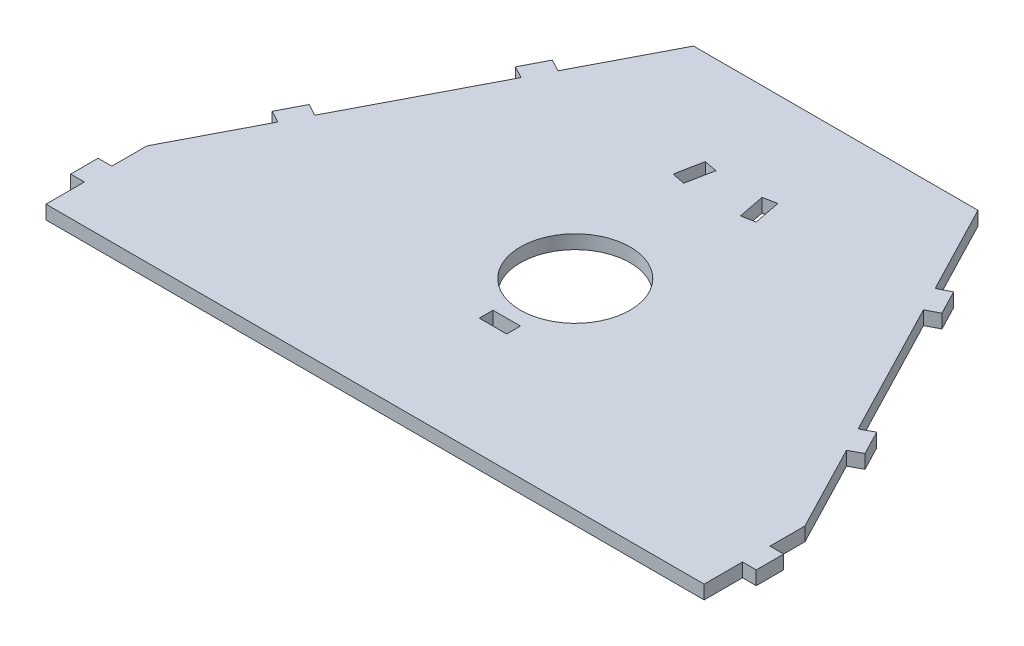
SolidWorks part; units mm, degrees
ref_plane "Front Plane" through (0, 0, 0) normal (0, 0, 1) x (1, 0, 0)
ref_plane "Top Plane" through (0, 0, 0) normal (0, 1, 0) x (1, 0, 0)
ref_plane "Right Plane" through (0, 0, 0) normal (1, 0, 0) x (0, 0, -1)
sketch "Sketch1" plane through (0, 0, 0) normal (0, 1, 0) x (1, 0, 0)
  line L30 (-57.5, 167.9473) -> (57.5, 167.9473)
  line L34 (-57.5, 167.9473) -> (-125, 37.9473)
  line L38 (-125, 37.9473) -> (-125, -0.0527)
  line L39 (-125, -0.0527) -> (125, -0.0527)
  line L40 (125, -0.0527) -> (125, 37.9473)
  line L41 (57.5, 167.9473) -> (125, 37.9473)
  point P0 (0, 167.9473)
  dimension "D1" = 250
  dimension "D2" = 38
  dimension "D3" = 130
  dimension "D4" = 115
  dimension "D5" = 146.4795
  dimension "D6" = 146.4795
  dimension "D7" = 38
extrude "Boss-Extrude1" add sketch "Sketch1" along normal blind 5
sketch "Sketch2" plane through (0, 5, 0) normal (0, 1, 0) x (1, 0, 0)
  line L0 (-103.4765, 79.4) -> (-99.0751, 77.0278)
  line L3 (-125, 23.9473) -> (-120, 23.9473)
  line L5 (-120, 13.9473) -> (-125, 13.9473)
  line L7 (-120, -0.0527) -> (-120, 13.9473)
  line L8 (5, 42.9473) -> (-5, 42.9473)
  line L24 (-125, -0.0527) -> (125, -0.0527) construction
  line L26 (-13.2264, 133.5998) -> (-15.1482, 123.7862)
  line L27 (-78.2497, 127.985) -> (-103.4765, 79.4)
  line L29 (-57.5, 167.9473) -> (-125, 37.9473) construction
  line L33 (-108.0839, 70.5265) -> (-103.6832, 68.1528)
  line L44 (-8.4111, 132.6568) -> (-10.3329, 122.8432)
  line L45 (-5, 42.9473) -> (-5, 47.9473)
  line L46 (-5, 47.9473) -> (5, 47.9473)
  line L47 (5, 47.9473) -> (5, 42.9473)
  line L48 (-13.2264, 133.5998) -> (-8.4111, 132.6568)
  line L49 (-15.1482, 123.7862) -> (-10.3329, 122.8432)
  line L50 (15.1482, 123.7862) -> (10.3329, 122.8432)
  line L51 (13.2264, 133.5998) -> (8.4111, 132.6568)
  line L52 (8.4111, 132.6568) -> (10.3329, 122.8432)
  line L53 (13.2264, 133.5998) -> (15.1482, 123.7862)
  line L54 (-73.8437, 125.6212) -> (-99.0751, 77.0278)
  line L55 (-103.6832, 68.1528) -> (-120, 36.7282)
  line L56 (-68.7427, 135.4431) -> (-51.8655, 167.9473)
  line L57 (57.5, 167.9473) -> (-57.5, 167.9473) construction
  line L62 (-78.2497, 127.985) -> (-77.7889, 128.8725)
  line L67 (-51.8655, 167.9473) -> (-57.5, 167.9473)
  line L68 (-108.0839, 70.5265) -> (-125, 37.9473)
  line L69 (-125, 13.9473) -> (-125, -0.0527)
  line L70 (-120, 23.9473) -> (-120, 36.7282)
  line L82 (-57.5, 167.9473) -> (-73.1807, 137.7474)
  line L83 (-125, 37.9473) -> (-125, 23.9473)
  line L84 (-125, -0.0527) -> (-120, -0.0527)
  line L94 (-73.1807, 137.7474) -> (-68.7427, 135.4431)
  line L95 (-77.7889, 128.8725) -> (-73.3518, 126.5686)
  line L96 (-73.8437, 125.6212) -> (-73.3518, 126.5686)
  line L98 (73.8437, 125.6212) -> (73.3518, 126.5686)
  line L99 (77.7889, 128.8725) -> (73.3518, 126.5686)
  line L100 (73.1807, 137.7474) -> (68.7427, 135.4431)
  line L101 (125, -0.0527) -> (120, -0.0527)
  line L102 (125, 37.9473) -> (125, 23.9473)
  line L103 (57.5, 167.9473) -> (73.1807, 137.7474)
  line L104 (120, 23.9473) -> (120, 36.7282)
  line L105 (125, 13.9473) -> (125, -0.0527)
  line L106 (108.0839, 70.5265) -> (125, 37.9473)
  line L107 (51.8655, 167.9473) -> (57.5, 167.9473)
  line L108 (78.2497, 127.985) -> (77.7889, 128.8725)
  line L109 (68.7427, 135.4431) -> (51.8655, 167.9473)
  line L110 (103.6832, 68.1528) -> (120, 36.7282)
  line L111 (73.8437, 125.6212) -> (99.0751, 77.0278)
  line L112 (108.0839, 70.5265) -> (103.6832, 68.1528)
  line L113 (78.2497, 127.985) -> (103.4765, 79.4)
  line L114 (120, -0.0527) -> (120, 13.9473)
  line L115 (120, 13.9473) -> (125, 13.9473)
  line L116 (125, 23.9473) -> (120, 23.9473)
  line L117 (103.4765, 79.4) -> (99.0751, 77.0278)
  circle A0 centre (0, 72.9473) radius 20
  dimension "D13" = 5
  dimension "D14" = 40
  dimension "D4" = 4.9068
  dimension "D5" = 14
  dimension "D6" = 10
  dimension "D7" = 5.0006
  dimension "D8" = 10
  dimension "D1" = 5
  dimension "D9" = 10
  dimension "D10" = 10
  dimension "D11" = 10
  dimension "D12" = 4.9995
  dimension "D15" = 5
  dimension "D16" = 5
  dimension "D17" = 10
  dimension "D18" = 5
  dimension "D19" = 5
  dimension "D20" = 10
  dimension "D24" = 10
  dimension "D25" = 5
  dimension "D26" = 42.9473
  dimension "D33" = 4.9068
extrude "Cut-Extrude1" cut sketch "Sketch2" against normal through all
